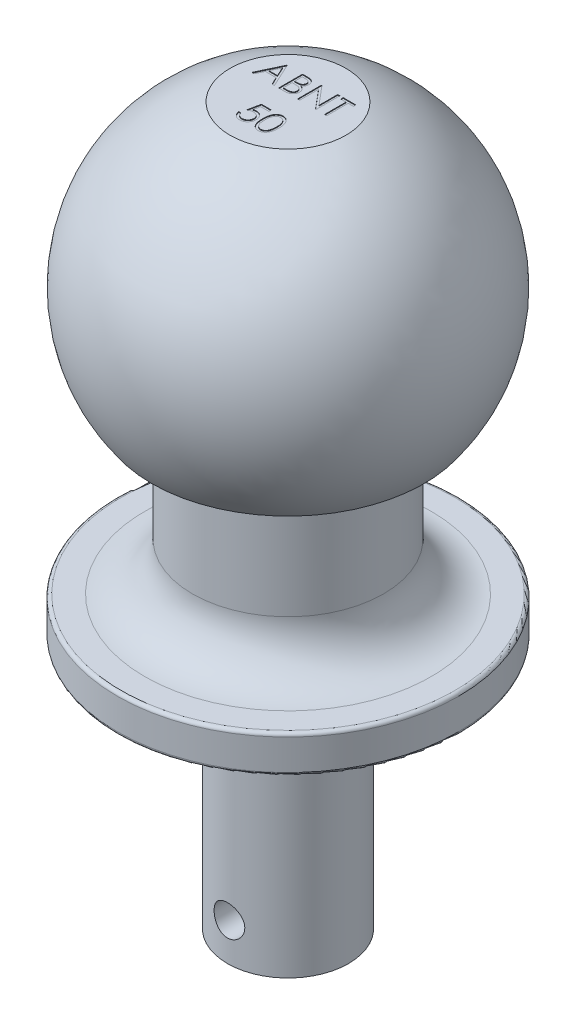
SolidWorks part; units mm, degrees
ref_plane "Plano frontal" through (0, 0, 0) normal (0, 0, 1) x (1, 0, 0)
ref_plane "Plano superior" through (0, 0, 0) normal (0, 1, 0) x (1, 0, 0)
ref_plane "Plano direito" through (0, 0, 0) normal (1, 0, 0) x (0, 0, -1)
sketch "Esboço1" plane through (0, 0, 0) normal (0, 0, 1) x (1, 0, 0)
  line L0 (0, 76.8681) -> (0, -78.7808) construction
  line L1 (8.5, 8.9961) -> (0, 8.9961)
  line L2 (19.9706, -29.5039) -> (14, -29.5039)
  line L3 (14, -29.5039) -> (14, -53.5039)
  line L4 (14, -53.5039) -> (25, -53.5039)
  line L5 (25, -53.5039) -> (25, -59.0039)
  line L6 (25, -59.0039) -> (9, -59.0039)
  line L7 (9, -59.0039) -> (9, -65.0039)
  line L8 (9, -65.0039) -> (8.875, -65.0039)
  line L9 (8.875, -65.0039) -> (8.875, -96.0039)
  line L10 (8.875, -96.0039) -> (0, -96.0039)
  line L11 (0, -96.0039) -> (0, 8.9961)
  arc A0 (19.9706, -29.5039) -> (8.5, 8.9961) centre (-0.0294, -14.5039) ccw
  dimension "D1" = 25
  dimension "D2" = 8.5
  dimension "D3" = 39
  dimension "D4" = 5.5
  dimension "D5" = 6
  dimension "D6" = 37
  dimension "D7" = 15
  dimension "D8" = 8.875
  dimension "D9" = 9
  dimension "D10" = 25
  dimension "D11" = 14
  dimension "D12" = 105
revolve "Revolução1" add sketch "Esboço1" angle 360 about L0
fillet "Filete1" radius 3 1 edges at (0, -29.5039, 14)
fillet "Filete2" radius 7 1 edges at (0, -53.5039, 14)
fillet "Filete3" radius 0.5 2 edges at (0, -59.0039, 25) (0, -53.5039, 25)
fillet "Filete4" radius 1 1 edges at (0, -59.0039, 9)
chamfer "Chanfro1" distance 1 angle 45 1 edges at (0, -96.0039, 8.875)
sketch "Esboço2" plane through (0, 8.9961, 0) normal (0, 1, 0) x (1, 0, 0)
  text T0 "ABNT\r\n   50"
sketch "Esboço3" plane through (0, -96.0039, 0) normal (0, -1, 0) x (1, 0, 0)
  line L1 (-11.3395, 10.7887) -> (11.3395, 10.7887)
  line L2 (-11.3395, 10.7887) -> (-11.3395, -10.7887)
  line L3 (-11.3395, -10.7887) -> (11.3395, -10.7887)
  line L4 (11.3395, 10.7887) -> (11.3395, -10.7887)
  line L5 (-11.3395, 10.7887) -> (11.3395, -10.7887) construction
  line L6 (-11.3395, -10.7887) -> (11.3395, 10.7887) construction
  point P0 (0, 0)
extrude "Ressalto-extrusão3" add sketch "Esboço3" against normal blind 15
sketch "Esboço4" plane through (0, 0, 10.7887) normal (0, 0, 1) x (1, 0, 0)
  line L0 (0, -96.0039) -> (0, -90.5039) construction
  line L1 (11.3395, -96.0039) -> (-11.3395, -96.0039) construction
  circle A0 centre (0, -90.5039) radius 2.25
extrude "Corte-extrusão1" cut sketch "Esboço4" against normal through all
sketch "Esboço5" plane through (0, -96.0039, 0) normal (0, -1, 0) x (1, 0, 0)
  line L1 (-13.2186, 13.0566) -> (13.2186, 13.0566)
  line L2 (-13.2186, 13.0566) -> (-13.2186, -13.0566)
  line L3 (-13.2186, -13.0566) -> (13.2186, -13.0566)
  line L4 (13.2186, 13.0566) -> (13.2186, -13.0566)
  line L5 (-13.2186, 13.0566) -> (13.2186, -13.0566) construction
  line L6 (-13.2186, -13.0566) -> (13.2186, 13.0566) construction
  circle A0 centre (0, 0) radius 8.875
  dimension "D1" = 17.75
extrude "Corte-extrusão2" cut sketch "Esboço5" against normal blind 17.75
extrude "Corte-extrusão3" cut sketch "Esboço2" against normal blind 0.1
